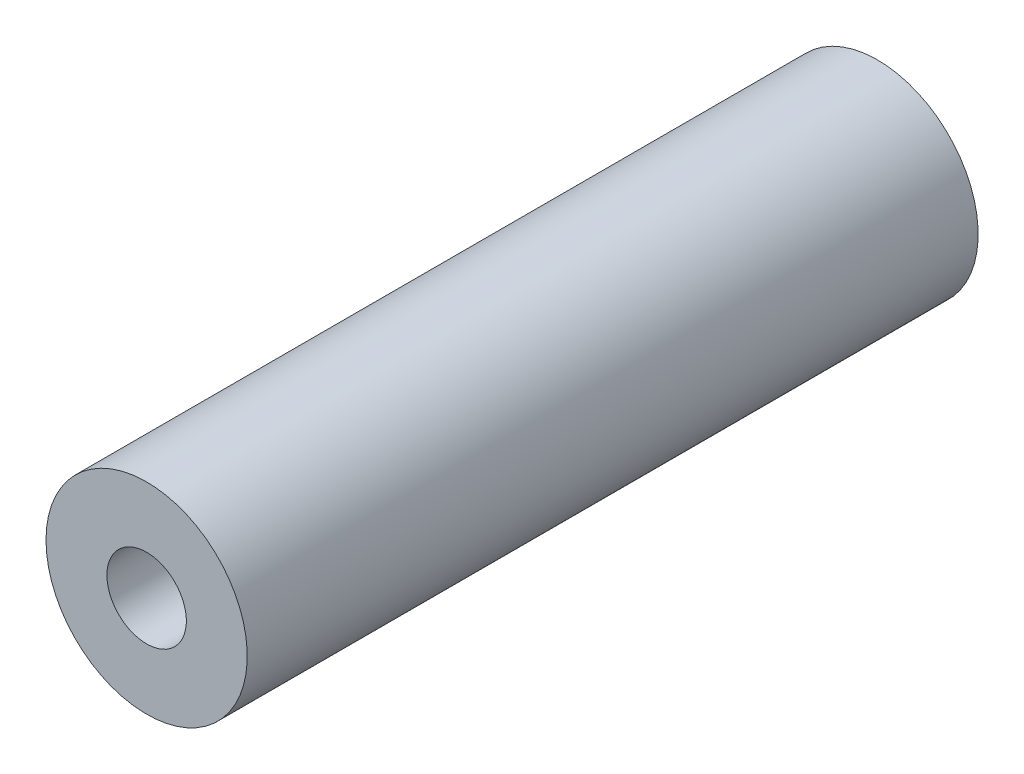
SolidWorks part; units mm, degrees
material "Nylon 101"
ref_plane "Front Plane" through (0, 0, 0) normal (0, 0, 1) x (1, 0, 0)
ref_plane "Top Plane" through (0, 0, 0) normal (0, 1, 0) x (1, 0, 0)
ref_plane "Right Plane" through (0, 0, 0) normal (1, 0, 0) x (0, 0, -1)
sketch "Sketch1" plane through (0, 0, 0) normal (0, 0, 1) x (1, 0, 0)
  circle A0 centre (0, 0) radius 2.0701
  circle A1 centre (0, 0) radius 5.2451
  dimension "D1" = 3.175
  dimension "D2" = 4.1402
extrude "Boss-Extrude1" add sketch "Sketch1" along normal blind 38.1
